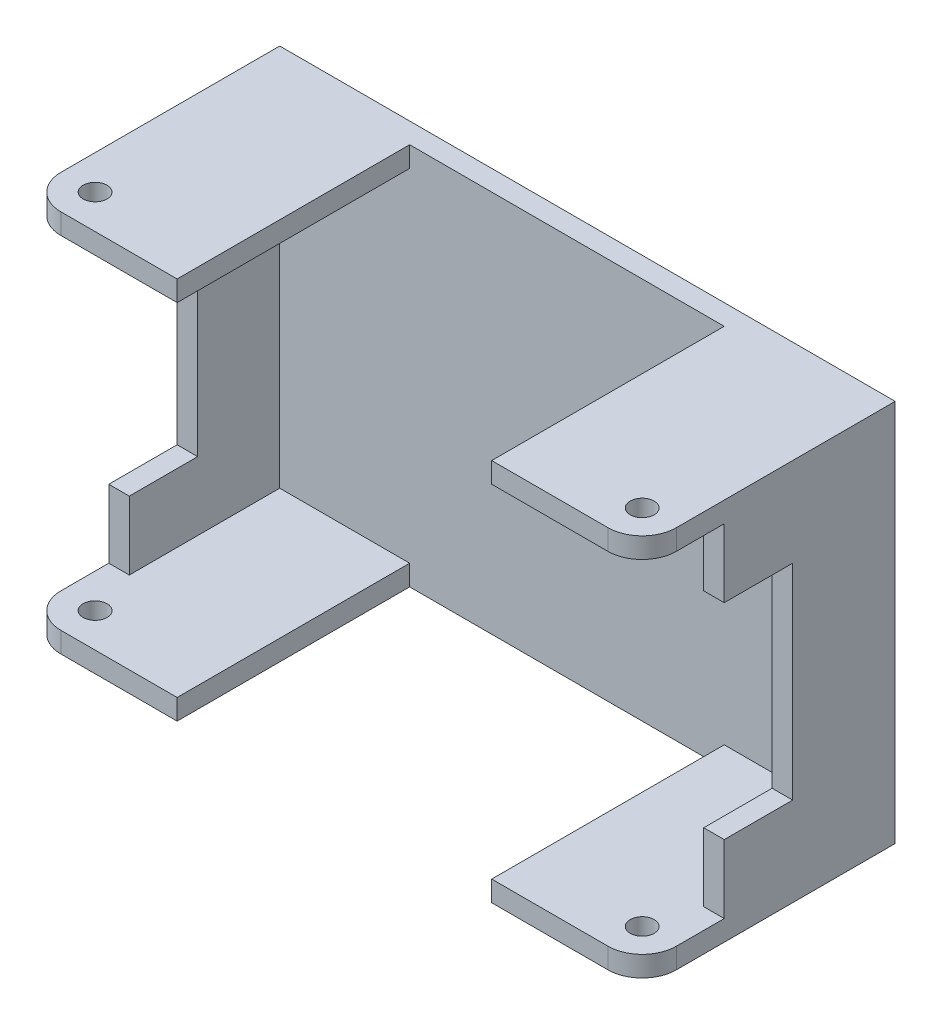
SolidWorks part; units mm, degrees
material "ABS"
ref_plane "Płaszczyzna przednia" through (0, 0, 0) normal (0, 0, 1) x (1, 0, 0)
ref_plane "Płaszczyzna górna" through (0, 0, 0) normal (0, 1, 0) x (1, 0, 0)
ref_plane "Płaszczyzna prawa" through (0, 0, 0) normal (1, 0, 0) x (0, 0, -1)
sketch "Szkic1" plane through (0, 0, 0) normal (0, 0, 1) x (1, 0, 0)
  line L1 (-45, -28) -> (45, -28)
  line L2 (-45, -28) -> (-45, 28)
  line L3 (-45, 28) -> (45, 28)
  line L4 (45, -28) -> (45, 28)
  line L5 (-45, -28) -> (45, 28) construction
  line L6 (-45, 28) -> (45, -28) construction
  point P0 (0, 0)
  dimension "D1" = 56
  dimension "D2" = 90
extrude "Dodanie-wyciągnięcie1" add sketch "Szkic1" along normal blind 3
sketch "Szkic2" plane through (0, 0, 3) normal (0, 0, 1) x (1, 0, 0)
  line L1 (-45, 28) -> (45, 28)
  line L2 (-45, 28) -> (-45, 25)
  line L3 (-45, 25) -> (45, 25)
  line L4 (45, 28) -> (45, 25)
  line L5 (45, -28) -> (45, 28) construction
  line L7 (45, -28) -> (-45, -28)
  line L8 (45, -28) -> (45, -25)
  line L9 (45, -25) -> (-45, -25)
  line L10 (-45, -28) -> (-45, -25)
  line L11 (-45, 28) -> (-45, -28) construction
  dimension "D1" = 3
  dimension "D2" = 90
  dimension "D4" = 90
extrude "Dodanie-wyciągnięcie2" add sketch "Szkic2" along normal blind 34
sketch "Szkic4" plane through (0, 28, 0) normal (0, 1, 0) x (1, 0, 0)
  line L0 (45, -37) -> (-45, -37) construction
  circle A0 centre (-40, -32) radius 1.75
  circle A1 centre (40, -32) radius 1.75
  point P4 (0, 0)
  point P5 (0, 0)
  point P6 (0, 0)
  dimension "D1" = 80
  dimension "D4" = 3.5
  dimension "D2" = 40
  dimension "D3" = 5
extrude "Wytnij-wyciągnięcie1" cut sketch "Szkic4" against normal through all
fillet "Zaokrąglenie1" radius 5 4 edges at (-45, -26.5, 37) (45, -26.5, 37) (45, 26.5, 37) (-45, 26.5, 37)
sketch "Szkic5" plane through (0, 28, 0) normal (0, 1, 0) x (1, 0, 0)
  line L0 (40, -37) -> (-40, -37) construction
  line L1 (-23, -3) -> (23, -3)
  line L2 (-23, -3) -> (-23, -43)
  line L3 (-23, -43) -> (23, -43)
  line L4 (23, -3) -> (23, -43)
  line L5 (0, 0) -> (0, -37) construction
  line L6 (45, 0) -> (-45, 0) construction
  dimension "D1" = 40
  dimension "D2" = 46
  dimension "D3" = 3
extrude "Wytnij-wyciągnięcie2" cut sketch "Szkic5" against normal through all
sketch "Szkic6" plane through (0, 0, 3) normal (0, 0, 1) x (1, 0, 0)
  line L1 (-45, 25) -> (-42, 25)
  line L2 (-45, 25) -> (-45, -25)
  line L3 (-45, -25) -> (-42, -25)
  line L4 (-42, 25) -> (-42, -25)
  line L5 (-23, -25) -> (-45, -25) construction
  line L7 (42, -25) -> (45, -25)
  line L8 (42, -25) -> (42, 25)
  line L9 (42, 25) -> (45, 25)
  line L10 (45, -25) -> (45, 25)
  line L11 (45, -25) -> (23, -25) construction
  dimension "D1" = 50
  dimension "D2" = 3
  dimension "D3" = 50
extrude "Dodanie-wyciągnięcie4" add sketch "Szkic6" along normal blind 12
sketch "Szkic7" plane through (0, 0, 15) normal (0, 0, 1) x (1, 0, 0)
  line L1 (-45, 15) -> (-42, 15)
  line L2 (-45, 15) -> (-45, -15)
  line L3 (-45, -15) -> (-42, -15)
  line L4 (-42, 15) -> (-42, -15)
  line L6 (-45, 25) -> (-45, -25) construction
  line L7 (-42, -25) -> (-42, 25) construction
  line L9 (42, 15) -> (45, 15)
  line L10 (42, 15) -> (42, -15)
  line L11 (42, -15) -> (45, -15)
  line L12 (45, 15) -> (45, -15)
  line L14 (42, 25) -> (42, -25) construction
  line L15 (45, -25) -> (45, 25) construction
  line L16 (-42, 0) -> (42, 0) construction
  line L19 (42, -25) -> (45, -25) construction
  line L20 (45, 25) -> (42, 25) construction
  line L21 (-45, -25) -> (-42, -25) construction
  line L22 (-42, -25) -> (-42, 25) construction
  line L23 (-42, 25) -> (-45, 25) construction
  line L24 (42, 25) -> (42, -25)
  line L25 (42, -25) -> (45, -25)
  line L26 (45, -25) -> (45, 25)
  line L27 (45, 25) -> (42, 25)
  line L28 (-45, 25) -> (-45, -25)
  line L29 (-45, -25) -> (-42, -25)
  line L30 (-42, -25) -> (-42, 25)
  line L31 (-42, 25) -> (-45, 25)
  line L32 (-40, 25) -> (-23, 25) construction
  line L33 (-23, -25) -> (-40, -25) construction
  line M7 (-45, 25) -> (-45, -25)
  line M8 (-45, -25) -> (-42, -25)
  line M9 (-42, -25) -> (-42, 25)
  line M10 (-42, 25) -> (-45, 25)
  dimension "D1" = 30
  dimension "D2" = 3
  dimension "D4" = 3
extrude "Dodanie-wyciągnięcie5" add sketch "Szkic7" along normal blind 10 contours L1 M7 M9 M10 | L3 M7 M8 M9 | L25 L26 L11 L24 | L26 L27 L24 L9
